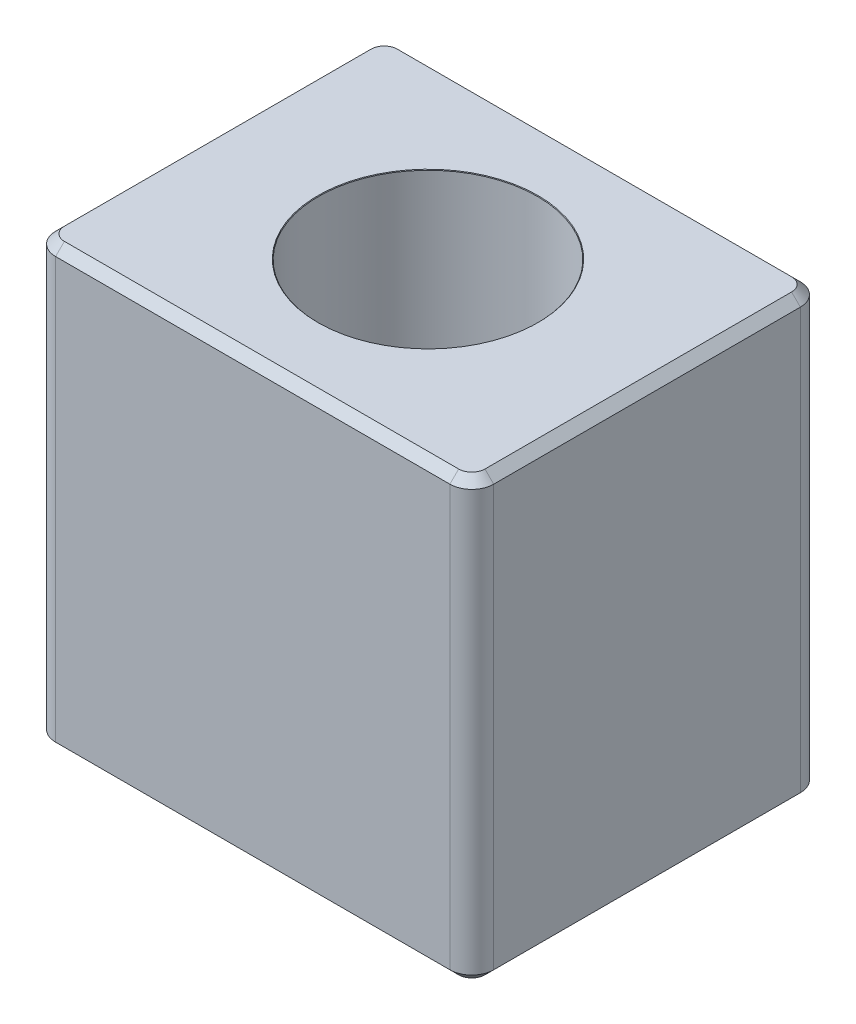
SolidWorks part; units mm, degrees
material "ABS"
ref_plane "Front Plane" through (0, 0, 0) normal (0, 0, 1) x (1, 0, 0)
ref_plane "Top Plane" through (0, 0, 0) normal (0, 1, 0) x (1, 0, 0)
ref_plane "Right Plane" through (0, 0, 0) normal (1, 0, 0) x (0, 0, -1)
sketch "Sketch1" plane through (0, 0, 0) normal (0, 0, 1) x (1, 0, 0)
  line L1 (10, -10) -> (-10, -10)
  line L2 (10, -10) -> (10, 10)
  line L3 (10, 10) -> (-10, 10)
  line L4 (-10, -10) -> (-10, 10)
  line L5 (10, -10) -> (-10, 10) construction
  line L6 (10, 10) -> (-10, -10) construction
  point P0 (0, 0)
  dimension "D1" = 20
  dimension "D2" = 20
extrude "Boss-Extrude1" add sketch "Sketch1" along normal blind 16
hole_wizard "CBORE for M5 Hex Socket Head Cap Screw1" positions "Sketch2" profile "Sketch4" counterbore size "M5" standard "DIN" end condition up to next
sketch "Sketch2" plane through (0, 10, 0) normal (0, 1, 0) x (1, 0, 0)
  line L0 (0, 0) -> (0, -16) construction
  line L1 (10, -16) -> (-10, -16) construction
  point P0 (0, -8)
  point P9 (0, -8)
sketch "Sketch4" plane through (0, 10, 8) normal (1, 0, 0) x (0, 0, 1)
  line L0 (0, 0) -> (0, 20)
  line L1 (0, 20) -> (2.75, 20)
  line L3 (2.75, 20) -> (2.75, 11)
  line L4 (5, 11) -> (2.75, 11)
  line L5 (5, 11) -> (5, 0.025)
  line L6 (5, 0.025) -> (5.025, 0)
  line L7 (5.025, 0) -> (0, 0)
  line L8 (-5, 0.025) -> (-5.025, 0) construction
  line L11 (0, -6.35) -> (0, 107.95) construction
  dimension "Thru Hole Dia." = 5.5
  dimension "Thru Hole Depth" = 20
  dimension "C'Bore Dia." = 10
  dimension "C'Bore Depth" = 11
  dimension "Near C'Sink Dia." = 10.05
  dimension "Near C'Sink Angle" = 90
fillet "Fillet1" radius 1 4 edges at (10, 0, 0) (10, 0, 16) (-10, 0, 0) (-10, 0, 16)
chamfer "Chamfer1" distance 0.4 angle 45 16 edges at (9.7071, 10, 15.7071) (0, 10, 16) (-9.7071, 10, 15.7071) (-10, 10, 8) (-9.7071, 10, 0.2929) (0, 10, 0) (9.7071, 10, 0.2929) (10, 10, 8) (-9.7071, -10, 0.2929) (-10, -10, 8) (-9.7071, -10, 15.7071) (0, -10, 16) (9.7071, -10, 15.7071) (10, -10, 8) (9.7071, -10, 0.2929) (0, -10, 0)
